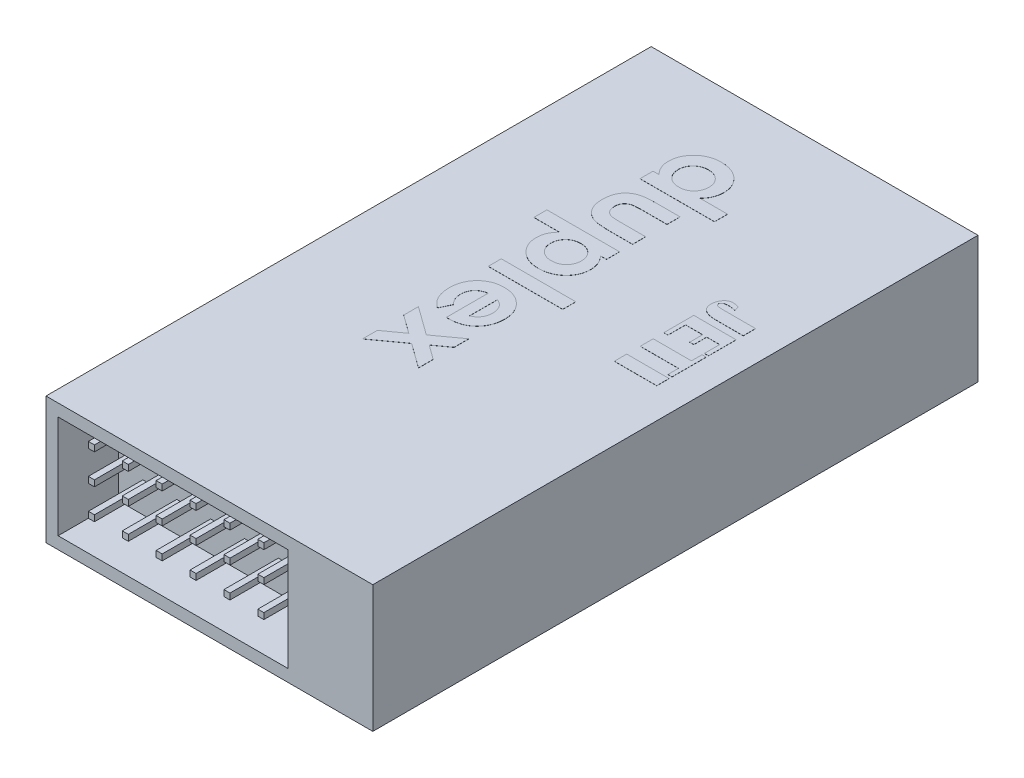
SolidWorks part; units mm, degrees
ref_plane "Front Plane" through (0, 0, 0) normal (0, 0, 1) x (1, 0, 0)
ref_plane "Top Plane" through (0, 0, 0) normal (0, 1, 0) x (1, 0, 0)
ref_plane "Right Plane" through (0, 0, 0) normal (1, 0, 0) x (0, 0, -1)
sketch "Sketch1" plane through (0, 0, 0) normal (0, 1, 0) x (1, 0, 0)
  line L1 (-16.4913, 9.4942) -> (10.5087, 9.4942)
  line L2 (-16.4913, 9.4942) -> (-16.4913, -40.5058)
  line L3 (-16.4913, -40.5058) -> (10.5087, -40.5058)
  line L4 (10.5087, 9.4942) -> (10.5087, -40.5058)
  dimension "D1" = 27
  dimension "D2" = 50
extrude "Boss-Extrude1" add sketch "Sketch1" along normal blind 10.5
sketch "Sketch2" plane through (0, 0, 40.5058) normal (0, 0, 1) x (1, 0, 0)
  line L0 (-16.4913, 10.5) -> (10.5087, 10.5) construction
  line L1 (-15.4913, 9.5) -> (3.5087, 9.5)
  line L2 (-15.4913, 9.5) -> (-15.4913, 1)
  line L3 (-15.4913, 1) -> (3.5087, 1)
  line L4 (3.5087, 9.5) -> (3.5087, 1)
  line L5 (-16.4913, 0) -> (10.5087, 0) construction
  line L6 (-16.4913, 10.5) -> (-16.4913, 0) construction
  dimension "D1" = 1
  dimension "D2" = 1
  dimension "D3" = 1
  dimension "D4" = 19
extrude "Cut-Extrude1" cut sketch "Sketch2" against normal blind 5
sketch "Sketch3" plane through (0, 0, 35.5058) normal (0, 0, 1) x (1, 0, 0)
  line L0 (-15.4913, 9.5) -> (-15.4913, 1) construction
  line L1 (-13.4913, 8.5) -> (-12.9913, 8.5)
  line L2 (-13.4913, 8.5) -> (-13.4913, 8)
  line L3 (-13.4913, 8) -> (-12.9913, 8)
  line L4 (-12.9913, 8.5) -> (-12.9913, 8)
  line L5 (3.5087, 9.5) -> (-15.4913, 9.5) construction
  dimension "D1" = 0.5
  dimension "D2" = 0.5
  dimension "D3" = 2
  dimension "D4" = 1
extrude "Boss-Extrude2" add sketch "Sketch3" along normal blind 4.5
pattern_linear "LPattern1" count 3 spacing 2.5 along (0, -1, 0) of "Boss-Extrude2"
pattern_linear "LPattern2" count 6 spacing 2.8 along (1, 0, 0) of "LPattern1", "Boss-Extrude2"
sketch "Sketch4" plane through (0, 0, -9.4942) normal (0, 0, -1) x (-1, 0, 0)
  line L0 (-10.5087, 10.5) -> (16.4913, 10.5) construction
  line L1 (-9.5087, 9.5) -> (15.4913, 9.5)
  line L2 (-9.5087, 9.5) -> (-9.5087, 1)
  line L3 (-9.5087, 1) -> (15.4913, 1)
  line L4 (15.4913, 9.5) -> (15.4913, 1)
  line L5 (-10.5087, 10.5) -> (-10.5087, 0) construction
  line L6 (-10.5087, 0) -> (16.4913, 0) construction
  line L7 (16.4913, 10.5) -> (16.4913, 0) construction
  dimension "D1" = 1
  dimension "D2" = 1
  dimension "D3" = 1
  dimension "D4" = 1
extrude "Cut-Extrude2" cut sketch "Sketch4" against normal blind 5
sketch "Sketch5" plane through (0, 0, -4.4942) normal (0, 0, -1) x (-1, 0, 0)
  line L0 (-9.5087, 9.5) -> (-9.5087, 1) construction
  line L1 (-8.0087, 7.7) -> (-7.5087, 7.7)
  line L2 (-8.0087, 7.7) -> (-8.0087, 7.2)
  line L3 (-8.0087, 7.2) -> (-7.5087, 7.2)
  line L4 (-7.5087, 7.7) -> (-7.5087, 7.2)
  line L5 (15.4913, 9.5) -> (-9.5087, 9.5) construction
  dimension "D1" = 0.5
  dimension "D2" = 0.5
  dimension "D3" = 1.5
  dimension "D4" = 1.8
extrude "Boss-Extrude3" add sketch "Sketch5" along normal blind 4.5
pattern_linear "LPattern3" count 3 spacing 2.2 along (0, -1, 0) of "Boss-Extrude3"
pattern_linear "LPattern4" count 8 spacing 3 along (-1, 0, 0) of "LPattern3", "Boss-Extrude3"
sketch "Sketch6" plane through (0, 10.5, 0) normal (0, 1, 0) x (1, 0, 0)
  line L0 (-7.4913, 4.4942) -> (-7.4913, -34.2009) construction
  line L1 (-16.4913, 9.4942) -> (-16.4913, -40.5058) construction
  line L2 (10.5087, 9.4942) -> (-16.4913, 9.4942) construction
  line L3 (4.5087, -5.5058) -> (4.5087, -27.5842) construction
  line L4 (10.5087, -40.5058) -> (10.5087, 9.4942) construction
  text T0 "duplex" font "Century Gothic" height 6
  text T1 "JETI" font "Britannic Bold" height 3.5
  point P11 (4.5087, -27.5842)
  dimension "D1" = 9
  dimension "D2" = 5
  dimension "D3" = 6
  dimension "D4" = 15
extrude "Boss-Extrude4" add sketch "Sketch6" along normal blind 0.01
